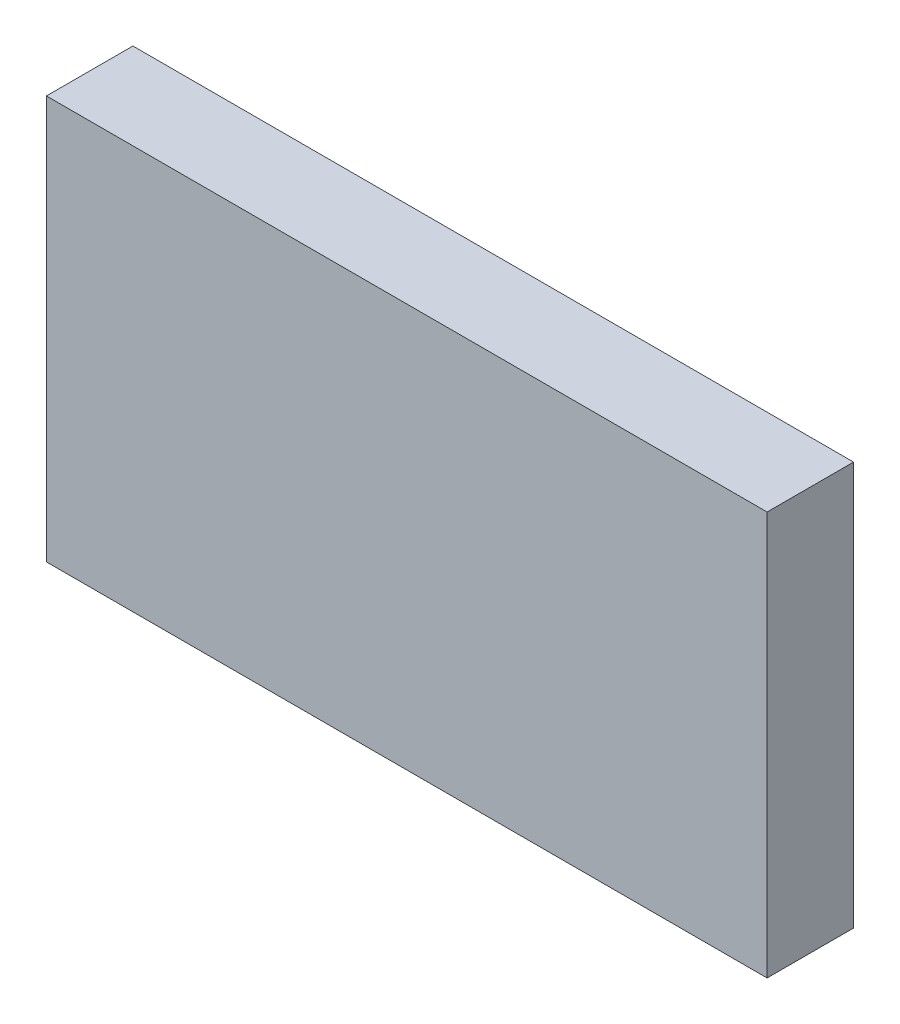
SolidWorks part; units mm, degrees
material "Oak"
ref_plane "Front" through (0, 0, 0) normal (0, 0, 1) x (1, 0, 0)
ref_plane "Top" through (0, 0, 0) normal (0, 1, 0) x (1, 0, 0)
ref_plane "Right" through (0, 0, 0) normal (1, 0, 0) x (0, 0, -1)
sketch "Sketch1" plane through (0, 0, 0) normal (0, 0, 1) x (1, 0, 0)
  line L1 (0, 0) -> (158.75, 0)
  line L2 (0, 0) -> (0, 88.9)
  line L3 (0, 88.9) -> (158.75, 88.9)
  line L4 (158.75, 0) -> (158.75, 88.9)
  dimension "D1" = 158.75
  dimension "D2" = 88.9
extrude "Boss-Extrude1" add sketch "Sketch1" along normal blind 19.05
